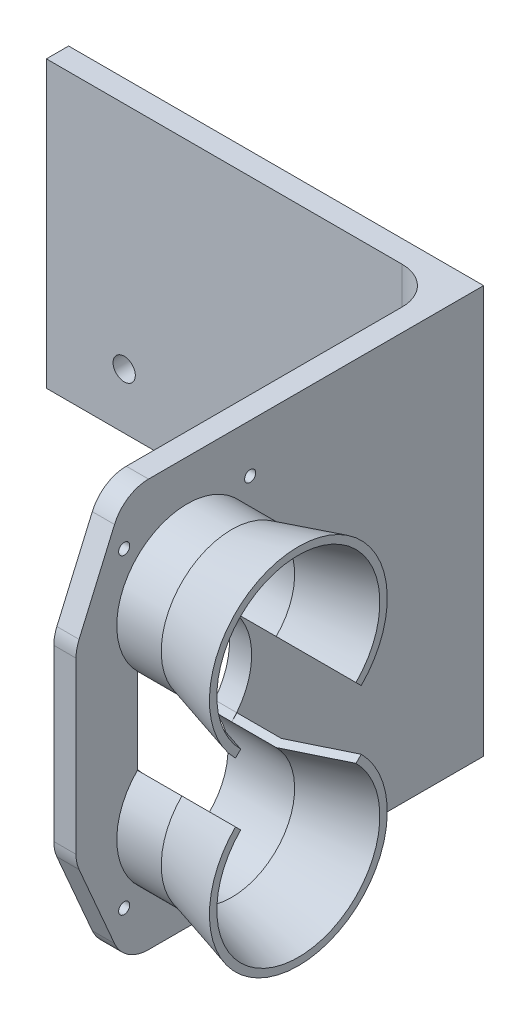
SolidWorks part; units mm, degrees
ref_plane "前视基准面" through (0, 0, 0) normal (0, 0, 1) x (1, 0, 0)
ref_plane "上视基准面" through (0, 0, 0) normal (0, 1, 0) x (1, 0, 0)
ref_plane "右视基准面" through (0, 0, 0) normal (1, 0, 0) x (0, 0, -1)
other "Configuration Table"
sketch "草图1" plane through (0, 0, 0) normal (0, 1, 0) x (1, 0, 0)
  line L0 (-30.1176, 27.2843) -> (25.8824, 27.2843)
  line L1 (25.8824, 27.2843) -> (25.8824, -27.7157)
  line L2 (25.8824, -27.7157) -> (22.8824, -27.7157)
  line L3 (22.8824, -27.7157) -> (22.8824, 24.2843)
  line L4 (22.8824, 24.2843) -> (-30.1176, 24.2843)
  line L5 (-30.1176, 24.2843) -> (-30.1176, 27.2843)
  dimension "D1" = 55
  dimension "D2" = 56
  dimension "D3" = 3
  dimension "D4" = 3
extrude "凸台-拉伸1" add sketch "草图1" along normal mid plane 55
ref_plane "基准面1" through (0, 0, -27.2843) normal (0, 0, -1) x (-1, 0, 0)
sketch "草图2" plane through (0, 0, -27.2843) normal (0, 0, -1) x (-1, 0, 0)
  line L0 (18.1176, -3.5) -> (1.1176, -3.5)
  line L1 (-25.8824, 27.5) -> (-25.8824, -27.5) construction
  line L2 (30.1176, 27.5) -> (30.1176, -27.5) construction
  line L3 (-25.8824, 27.5) -> (30.1176, 27.5) construction
  line L4 (30.1176, -11) -> (10.1176, -11)
  line L5 (10.1176, -11) -> (10.1176, -27.5)
  line L6 (-25.8824, -27.5) -> (30.1176, -27.5) construction
  line L7 (10.1176, -27.5) -> (30.1176, -27.5)
  line L8 (30.1176, -27.5) -> (30.1176, -11)
  line L9 (-25.8824, 0) -> (30.1176, 0)
  line L10 (10.1176, 27.5) -> (30.1176, 27.5)
  line L11 (10.1176, 11) -> (10.1176, 27.5)
  line L12 (30.1176, 11) -> (10.1176, 11)
  line L13 (30.1176, 27.5) -> (30.1176, 11)
  circle A2 centre (19.6176, -3.5) radius 1.5
  circle A3 centre (-0.3824, -3.5) radius 1.5
  circle A4 centre (19.6176, 3.5) radius 1.5
  circle A5 centre (-0.3824, 3.5) radius 1.5
  dimension "D3" = 3
  dimension "D4" = 3
  dimension "D1" = 31
  dimension "D2" = 31
  dimension "D5" = 10.5
  dimension "D6" = 25.5
  dimension "D7" = 7.5
  dimension "D8" = 20
ref_plane "基准面2" through (25.8824, 0, 0) normal (1, 0, 0) x (0, 0, -1)
sketch "草图3" plane through (25.8824, 0, 0) normal (1, 0, 0) x (0, 0, -1)
  line L0 (-27.7157, 27.5) -> (-27.7157, -27.5) construction
  line L1 (-22.7157, 22.5) -> (-2.7157, 22.5)
  line L2 (-22.7157, 22.5) -> (-22.7157, -22.5)
  line L3 (-22.7157, -22.5) -> (-2.7157, -22.5)
  line L4 (-2.7157, 22.5) -> (-2.7157, -22.5)
  line L5 (-22.7157, 22.5) -> (-2.7157, -22.5) construction
  line L6 (-22.7157, -22.5) -> (-2.7157, 22.5) construction
  line L7 (-12.7157, 22.5) -> (-12.7157, 22)
  line L8 (-12.7157, 12.5) -> (-6.7053, 6.4896)
  line L9 (-12.7157, 12.5) -> (-18.7261, 6.4896)
  line L10 (-12.7157, -12.5) -> (-18.7261, -6.4896)
  line L11 (-12.7157, -12.5) -> (-6.7053, -6.4896)
  line L12 (-12.7157, -22) -> (-12.7157, -22.5)
  line L13 (-12.7157, -4) -> (-12.7157, -21)
  line L14 (-12.7157, 3) -> (-12.7157, -3)
  line L15 (-12.7157, 21) -> (-12.7157, 4)
  line L16 (-22.7157, 0) -> (-2.7157, 0)
  line L17 (-18.7261, 6.4896) -> (-19.3945, 5.744)
  line L18 (-6.7053, 6.4896) -> (-6.0369, 5.744)
  line L19 (-6.7053, -6.4896) -> (-6.0369, -5.744)
  line L20 (-18.7261, -6.4896) -> (-19.3945, -5.744)
  line L21 (-19.3945, 5.744) -> (-19.3945, -5.744)
  line L23 (-27.7157, 27.5) -> (27.2843, 27.5) construction
  line L25 (-23.7833, 27.5) -> (-27.7157, 27.5)
  line L26 (-27.7157, 27.5) -> (-27.7157, 23.5676)
  line L27 (-27.7157, -23.5676) -> (-27.7157, -27.5)
  line L28 (-27.7157, -27.5) -> (-23.7833, -27.5)
  line L30 (-27.7157, 23.5676) -> (-27.7157, 20.2498)
  line L31 (-23.7833, 27.5) -> (-21.2157, 27.5)
  line L32 (-27.7157, -23.5676) -> (-27.7157, -20.2498)
  line L33 (-27.7157, -27.5) -> (-27.7157, -23.5676)
  line L35 (-23.7833, -27.5) -> (-21.2157, -27.5)
  line L36 (-21.2157, 27.5) -> (-27.7157, 12.5)
  line L37 (-27.7157, 12.5) -> (-27.7157, 20.2498)
  line L38 (-21.2157, -27.5) -> (-27.7157, -12.5)
  line L39 (-27.7157, -12.5) -> (-27.7157, -20.2498)
  circle A0 centre (-12.7157, 12.5) radius 8.5
  circle A1 centre (-12.7157, -12.5) radius 8.5
  arc A2 (-6.0369, 5.744) -> (-6.0369, -5.744) centre (-13.1949, 0) cw
  circle A4 centre (-12.7157, 12.5) radius 9.5
  circle A5 centre (-12.7157, -12.5) radius 9.5
  circle A6 centre (-4.2157, -21) radius 0.75
  circle A7 centre (-21.2157, -21) radius 0.75
  circle A8 centre (-4.2157, 21) radius 0.75
  circle A9 centre (-21.2157, 21) radius 0.75
  point P0 (0, 0)
  dimension "D6" = 17
  dimension "D7" = 17
  dimension "D8" = 19
  dimension "D9" = 19
  dimension "D11" = 1.5
  dimension "D1" = 45
  dimension "D2" = 20
  dimension "D3" = 5
  dimension "D4" = 10
  dimension "D5" = 10
  dimension "D10" = 1.5
  dimension "D12" = 1.5
  dimension "D13" = 7.2502
  dimension "D14" = 6.5
extrude "切除-拉伸3" cut sketch "草图3" against normal blind 3
ref_plane "基准面3" through (32.8824, 0, 0) normal (1, 0, 0) x (0, 0, -1)
sketch "草图4" plane through (32.8824, 0, 0) normal (1, 0, 0) x (0, 0, -1)
  circle A0 centre (-12.7157, 12.5) radius 12
  circle A1 centre (-12.7157, 12.5) radius 11
ref_plane "基准面4" through (0, 0, 12.7157) normal (0, 0, 1) x (0, -1, 0)
sketch "草图5" plane through (0, 0, 12.7157) normal (0, 0, 1) x (0, -1, 0)
  line L0 (-3, 25.8824) -> (-22, 25.8824) construction
  line L2 (-3, 25.8824) -> (-22, 25.8824)
  line L4 (-3, 25.8824) -> (-22, 25.8824)
  line L6 (-22, 25.8824) -> (-21, 25.8824)
  line L9 (-12.5, 32.8824) -> (-12.5, 25.8824)
  line L10 (-21, 25.8824) -> (-21, 31.8824)
  line L12 (-22, 25.8824) -> (-22, 31.8824)
  line L14 (-21, 31.8824) -> (-23.5, 40.8824)
  line L15 (-23.5, 40.8824) -> (-24.5, 40.8824)
  line L16 (-24.5, 40.8824) -> (-22, 31.8824)
  dimension "D1" = 6
  dimension "D2" = 9
revolve "旋转1" add sketch "草图5" angle 135 about L9
mirror "镜向1" about plane through (0, 0, 0) normal (0, 1, 0) of "旋转1"
mirror "镜向2" about plane through (0, 0, 12.7157) normal (0, 0, 1) of "旋转1"
mirror "镜向3" about plane through (0, 0, 12.7157) normal (0, 0, 1) of "镜向1"
extrude "切除-拉伸4" cut sketch "草图2" against normal blind 3 contours A3 | L7 L8 L4 L5 | A2
fillet "圆角1" radius 5 1 edges at (22.8824, 0, -24.2843)
fillet "圆角2" radius 5 4 edges at (24.3824, -27.5, 21.2157) (24.3824, -12.5, 27.7157) (24.3824, 27.5, 21.2157) (24.3824, 12.5, 27.7157)
